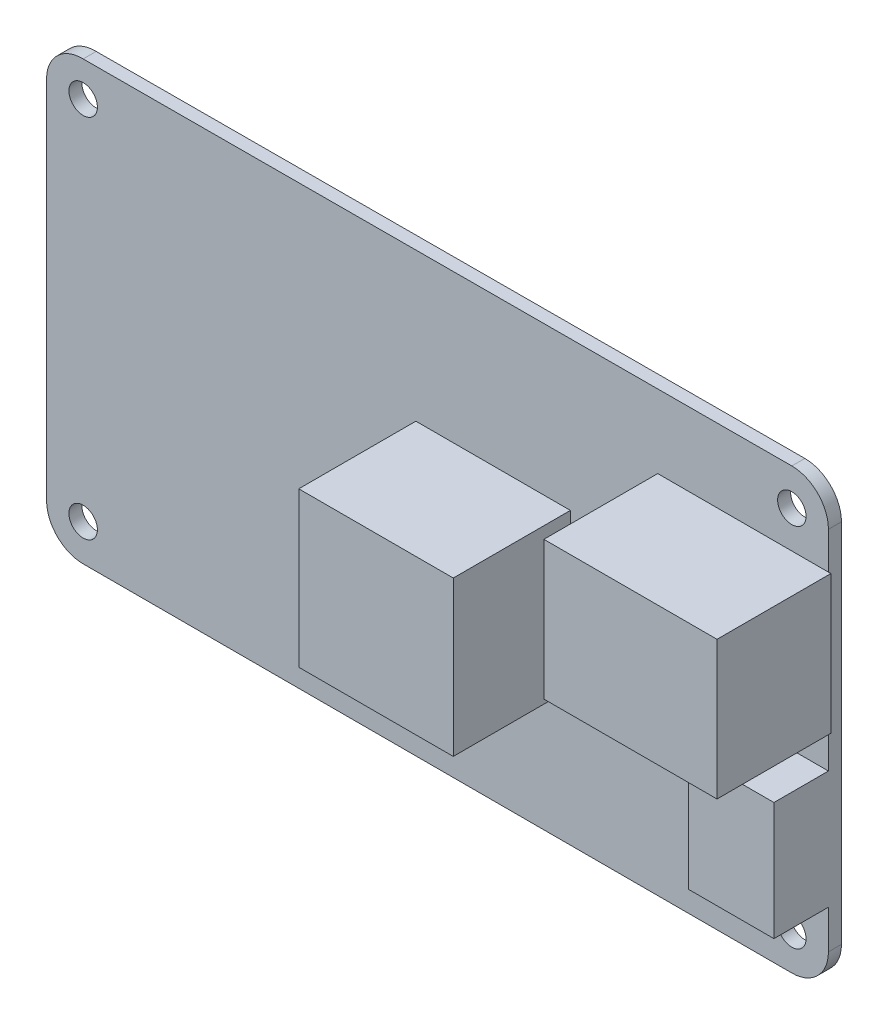
SolidWorks part; units mm, degrees
ref_plane "Front Plane" through (0, 0, 0) normal (0, 0, 1) x (1, 0, 0)
ref_plane "Top Plane" through (0, 0, 0) normal (0, 1, 0) x (1, 0, 0)
ref_plane "Right Plane" through (0, 0, 0) normal (1, 0, 0) x (0, 0, -1)
sketch "pcb" plane through (0, 0, -31.4284) normal (0, 0, 1) x (1, 0, 0)
  line L0 (91.8508, -91.4513) -> (91.8508, -136.4513)
  line L1 (87.3508, -140.9513) -> (0.2108, -140.9513)
  line L2 (-4.2892, -136.4513) -> (-4.2892, -91.4513)
  line L3 (87.3508, -86.9513) -> (0.2108, -87.1809)
  line L4 (-242.3949, -87.1809) -> (70.1051, -87.1809) construction
  circle A0 centre (87.3508, -136.4513) radius 1.75
  circle A1 centre (87.3508, -91.4513) radius 1.75
  circle A2 centre (0.2108, -91.4513) radius 1.75
  circle A3 centre (0.2108, -136.4513) radius 1.75
  arc A4 (87.3508, -140.9513) -> (91.8508, -136.4513) centre (87.3508, -136.4513) ccw
  arc A5 (87.3508, -86.9513) -> (91.8508, -91.4513) centre (87.3508, -91.4513) cw
  circle A6 centre (87.3508, -136.4513) radius 4.5 construction
  arc A7 (91.6807, -137.6771) -> (91.6807, -135.2256) centre (87.3508, -136.4513) ccw construction
  arc A8 (-4.2892, -136.4513) -> (0.2108, -140.9513) centre (0.2108, -136.4513) ccw
  circle A9 centre (0.2108, -136.4513) radius 4.5 construction
  circle A12 centre (87.3508, -91.4513) radius 4.5 construction
  arc A13 (-2.805, -88.1114) -> (3.2266, -88.1114) centre (0.2108, -91.4513) ccw construction
  arc A14 (-4.2892, -91.4513) -> (0.2108, -87.1809) centre (0.096, -91.5661) cw
extrude "board" add sketch "pcb" along normal blind 1.6
sketch "gige" plane through (0, 0, -29.8284) normal (0, 0, 1) x (1, 0, 0)
  line L0 (87.3508, -91.4513) -> (80.434, -91.4513) construction
  line L1 (70.8608, -113.0213) -> (92.1508, -113.0213)
  line L2 (70.8608, -113.0213) -> (70.8608, -96.0113)
  line L3 (70.8608, -96.0113) -> (92.1508, -96.0113)
  line L4 (92.1508, -113.0213) -> (92.1508, -96.0113)
  line L5 (91.8508, -136.4513) -> (91.8508, -91.4513) construction
  dimension "D1" = 4.56
  dimension "D2" = 20.99
  dimension "D3" = 0.3
  dimension "D4" = 17.01
extrude "ethernetport" add sketch "gige" along normal blind 14
sketch "hdmi" plane through (0, 0, -29.8284) normal (0, 0, 1) x (1, 0, 0)
  line L0 (87.3508, -136.4513) -> (81.831, -136.4513) construction
  line L1 (91.8508, -131.6913) -> (81.3508, -131.6913)
  line L2 (91.8508, -131.6913) -> (91.8508, -117.1913)
  line L3 (91.8508, -117.1913) -> (81.3508, -117.1913)
  line L4 (81.3508, -131.6913) -> (81.3508, -117.1913)
  line L5 (91.8508, -136.4513) -> (91.8508, -113.0213) construction
  dimension "D1" = 4.76
  dimension "D2" = 0
  dimension "D3" = 14.5
  dimension "D4" = 10.5
extrude "hdmiport" add sketch "hdmi" along normal blind 6.7
sketch "Sketch9" plane through (0, 0, -29.8284) normal (0, 0, 1) x (1, 0, 0)
  line L0 (91.8508, -117.1913) -> (91.8508, -113.0213) construction
  line L1 (60.1208, -124.3025) -> (41.1208, -124.3025)
  line L2 (60.1208, -124.3025) -> (60.1208, -105.3025)
  line L3 (60.1208, -105.3025) -> (41.1208, -105.3025)
  line L4 (41.1208, -124.3025) -> (41.1208, -105.3025)
  line L5 (81.6051, -141.0625) -> (-238.936, -141.0625) construction
  dimension "D1" = 31.73
  dimension "D2" = 19
  dimension "D3" = 19
  dimension "D4" = 16.76
extrude "FPGAandFan" add sketch "Sketch9" along normal blind 14.4
